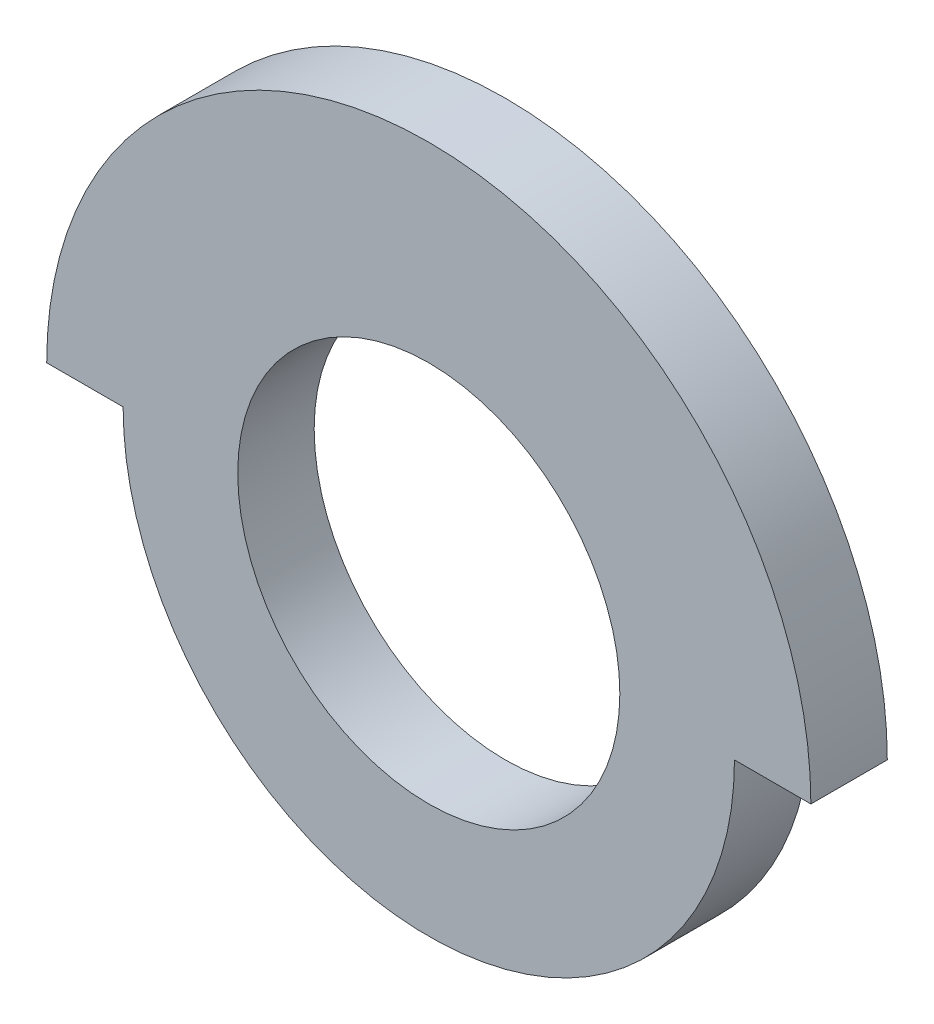
SolidWorks part; units mm, degrees
ref_plane "Front Plane" through (0, 0, 0) normal (0, 0, 1) x (1, 0, 0)
ref_plane "Top Plane" through (0, 0, 0) normal (0, 1, 0) x (1, 0, 0)
ref_plane "Right Plane" through (0, 0, 0) normal (1, 0, 0) x (0, 0, -1)
sketch "Sketch1" plane through (0, 0, 0) normal (0, 0, 1) x (1, 0, 0)
  line L0 (-10, 0) -> (-8, 0)
  line L1 (8, 0) -> (10, 0)
  arc A0 (10, 0) -> (-10, 0) centre (0, 0) ccw
  circle A1 centre (0, 0) radius 5
  arc A2 (-8, 0) -> (8, 0) centre (0, 0) ccw
  circle A3 centre (0, 0) radius 10 construction
  circle A4 centre (0, 0) radius 8 construction
  dimension "D1" = 20
  dimension "D2" = 10
  dimension "D3" = 2
extrude "Boss-Extrude1" add sketch "Sketch1" along normal blind 2
